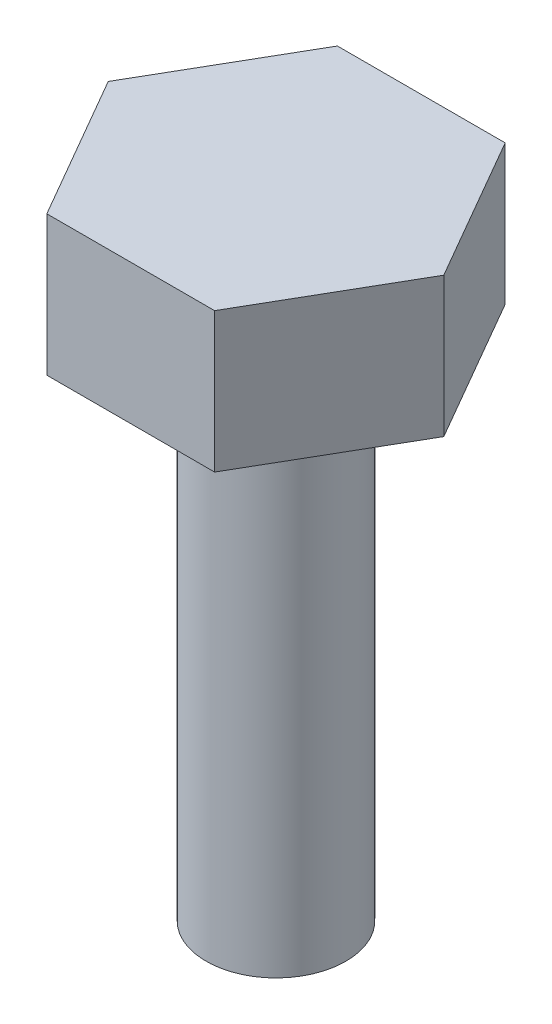
SolidWorks part; units mm, degrees
ref_plane "Front Plane" through (0, 0, 0) normal (0, 0, 1) x (1, 0, 0)
ref_plane "Top Plane" through (0, 0, 0) normal (0, 1, 0) x (1, 0, 0)
ref_plane "Right Plane" through (0, 0, 0) normal (1, 0, 0) x (0, 0, -1)
sketch "Sketch1" plane through (0, 0, 0) normal (0, 1, 0) x (1, 0, 0)
  line L1 (15.24, 0) -> (7.62, 13.1982)
  line L2 (7.62, 13.1982) -> (-7.62, 13.1982)
  line L3 (-7.62, 13.1982) -> (-15.24, 0)
  line L4 (-15.24, 0) -> (-7.62, -13.1982)
  line L5 (-7.62, -13.1982) -> (7.62, -13.1982)
  line L6 (7.62, -13.1982) -> (15.24, 0)
  circle A0 centre (0, 0) radius 13.1982 construction
  dimension "D1" = 15.24
extrude "Boss-Extrude1" add sketch "Sketch1" along normal blind 12.7
sketch "Sketch2" plane through (0, 0, 0) normal (0, -1, 0) x (1, 0, 0)
  circle A0 centre (0, 0) radius 6.35
  dimension "D1" = 12.7
extrude "Boss-Extrude2" add sketch "Sketch2" along normal blind 45.72
